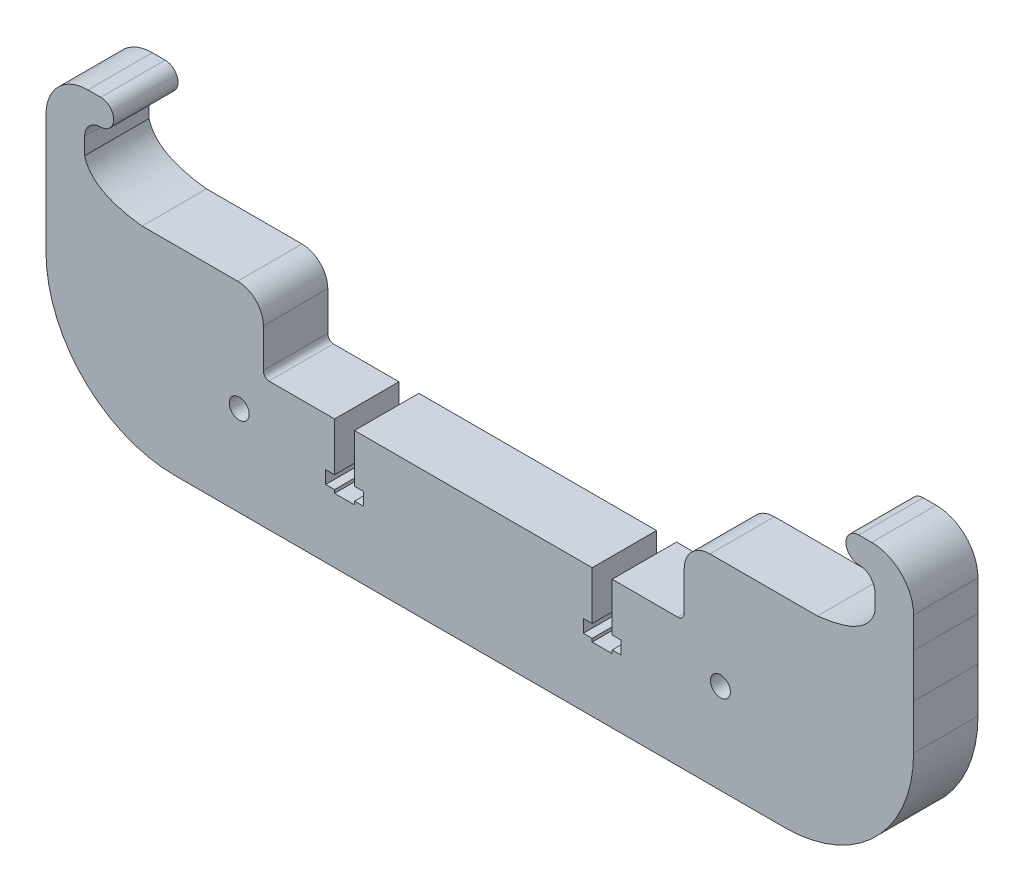
SolidWorks part; units mm, degrees
ref_plane "Płaszczyzna przednia" through (0, 0, 0) normal (0, 0, 1) x (1, 0, 0)
ref_plane "Płaszczyzna górna" through (0, 0, 0) normal (0, 1, 0) x (1, 0, 0)
ref_plane "Płaszczyzna prawa" through (0, 0, 0) normal (1, 0, 0) x (0, 0, -1)
sketch "Szkic1" plane through (0, 0, 0) normal (0, 0, 1) x (1, 0, 0)
  line L7 (587.4141, -426.2962) -> (650.8826, -426.2962)
  line L11 (552.8031, -407.6962) -> (552.8031, -419.2962)
  line L12 (561.3031, -401.1962) -> (559.3031, -401.1962)
  line L13 (567.725, -415.2962) -> (582.5551, -415.2962)
  line L14 (586.5551, -425.2962) -> (586.5551, -419.2962)
  line L15 (651.8852, -425.2936) -> (651.8852, -419.2962)
  line L16 (672.5705, -415.2962) -> (655.8852, -415.2962)
  line L17 (681.4924, -407.6962) -> (681.4924, -410.3096)
  line L18 (678.9924, -401.1962) -> (680.9924, -401.1962)
  line L20 (687.4924, -407.6962) -> (687.4924, -412.4993)
  line L21 (687.4978, -419.2962) -> (687.4924, -412.4993)
  line L22 (572.8031, -439.2962) -> (667.4978, -439.2962) construction
  line L23 (558.8031, -407.6962) -> (558.8031, -410.3096)
  line L28 (572.8031, -439.2962) -> (667.4978, -439.2962)
  arc A3 (667.4978, -439.2962) -> (687.4978, -419.2962) centre (667.4978, -419.2962) ccw construction
  arc A5 (552.8031, -419.2962) -> (572.8031, -439.2962) centre (572.8031, -419.2962) ccw construction
  arc A6 (667.4978, -439.2962) -> (687.4978, -419.2962) centre (667.4978, -419.2962) ccw
  arc A7 (552.8031, -419.2962) -> (572.8031, -439.2962) centre (572.8031, -419.2962) ccw
  arc A12 (559.3031, -401.1962) -> (552.8031, -407.6962) centre (559.3031, -407.6962) ccw
  arc A13 (561.3031, -405.1962) -> (561.3031, -401.1962) centre (561.3031, -403.1962) ccw
  arc A14 (561.3031, -405.1962) -> (558.8031, -407.6962) centre (561.3031, -407.6962) ccw
  arc A15 (586.5551, -419.2962) -> (582.5551, -415.2962) centre (582.5551, -419.2962) ccw
  arc A16 (655.8852, -415.2962) -> (651.8852, -419.2962) centre (655.8852, -419.2962) ccw
  arc A17 (681.4924, -407.6962) -> (678.9924, -405.1962) centre (678.9924, -407.6962) ccw
  arc A18 (678.9924, -401.1962) -> (678.9924, -405.1962) centre (678.9924, -403.1962) ccw
  arc A19 (687.4924, -407.6962) -> (680.9924, -401.1962) centre (680.9924, -407.6962) ccw
  arc A20 (651.8852, -425.2936) -> (650.8826, -426.2962) centre (650.8826, -425.2936) cw
  arc A21 (586.5551, -425.2962) -> (587.4141, -426.2962) centre (587.4846, -425.3667) ccw
  parabola Q2 (567.725, -415.2962) -> (558.8031, -410.3096) focus (561.3063, -410.1181) apex (559.1464, -411.2024)
  parabola Q3 (672.5705, -415.2962) -> (681.4924, -410.3096) focus (678.9892, -410.1181) apex (681.1491, -411.2024)
  point P0 (567.8031, -401.1962)
  point P20 (567.8031, -405.1962)
  point P21 (559.3031, -405.1962)
  point P30 (679.1031, -405.1962)
  point P31 (670.6031, -405.1962)
extrude "Dodanie-wyciągnięcie1" add sketch "Szkic1" along normal blind 10 contours L7 A20 L15 A16 L16 Q3 L17 A17 A18 L18 A19 L20 L21 A6 L28 A7 L11 A12 L12 A13 A14 L23 Q2 L13 A15 L14 A21
sketch "Szkic2" plane through (0, 0, 10) normal (0, 0, 1) x (1, 0, 0)
  line L0 (687.4978, -419.2962) -> (687.4924, -412.4993) construction
  line L1 (552.8031, -407.6962) -> (552.8031, -419.2962) construction
  circle A2 centre (657.508, -432.2754) radius 1.55
  circle A3 centre (582.8031, -432.2962) radius 1.55
  dimension "D1" = 30
  dimension "D2" = 30
extrude "Wytnij-wyciągnięcie1" cut sketch "Szkic2" against normal blind 10
sketch "Szkic3" plane through (0, 0, 0) normal (0, 0, -1) x (-1, 0, 0)
  line L0 (-600.6991, -426.2962) -> (-600.6991, -433.7962) construction
  line L1 (-597.5991, -433.7962) -> (-597.5991, -426.2962) construction
  line L2 (-600.6991, -433.7962) -> (-602.0741, -433.7962) construction
  line L3 (-602.0741, -433.7962) -> (-602.0741, -435.7962) construction
  line L4 (-602.0741, -435.7962) -> (-600.6991, -435.7962) construction
  line L5 (-600.6991, -435.7962) -> (-600.6991, -436.2962) construction
  line L6 (-600.6991, -436.2962) -> (-597.5991, -436.2962) construction
  line L7 (-597.5991, -435.7962) -> (-596.2241, -435.7962) construction
  line L8 (-597.5991, -436.2962) -> (-597.5991, -435.7962) construction
  line L9 (-596.2241, -435.7962) -> (-596.2241, -433.7962) construction
  line L10 (-596.2241, -433.7962) -> (-597.5991, -433.7962) construction
  line L11 (-600.6991, -426.2962) -> (-600.6991, -433.7962)
  line L12 (-597.5991, -433.7962) -> (-597.5991, -426.2962)
  line L13 (-600.6991, -433.7962) -> (-602.0741, -433.7962)
  line L14 (-602.0741, -433.7962) -> (-602.0741, -435.7962)
  line L15 (-602.0741, -435.7962) -> (-600.6991, -435.7962)
  line L16 (-600.6991, -435.7962) -> (-600.6991, -436.2962)
  line L17 (-600.6991, -436.2962) -> (-597.5991, -436.2962)
  line L18 (-597.5991, -435.7962) -> (-596.2241, -435.7962)
  line L19 (-597.5991, -436.2962) -> (-597.5991, -435.7962)
  line L20 (-596.2241, -435.7962) -> (-596.2241, -433.7962)
  line L21 (-596.2241, -433.7962) -> (-597.5991, -433.7962)
  line L22 (-640.6991, -426.2962) -> (-640.6991, -433.7962) construction
  line L23 (-640.6991, -433.7962) -> (-642.0741, -433.7962) construction
  line L24 (-642.0741, -433.7962) -> (-642.0741, -435.7962) construction
  line L25 (-642.0741, -435.7962) -> (-640.6991, -435.7962) construction
  line L26 (-640.6991, -435.7962) -> (-640.6991, -436.2962) construction
  line L27 (-640.6991, -436.2962) -> (-637.5991, -436.2962) construction
  line L28 (-637.5991, -436.2962) -> (-637.5991, -435.7962) construction
  line L29 (-637.5991, -435.7962) -> (-636.2241, -435.7962) construction
  line L30 (-636.2241, -435.7962) -> (-636.2241, -433.7962) construction
  line L31 (-636.2241, -433.7962) -> (-637.5991, -433.7962) construction
  line L32 (-637.5991, -433.7962) -> (-637.5991, -426.2962) construction
  line L33 (-640.6991, -426.2962) -> (-640.6991, -433.7962)
  line L34 (-640.6991, -433.7962) -> (-642.0741, -433.7962)
  line L35 (-642.0741, -433.7962) -> (-642.0741, -435.7962)
  line L36 (-642.0741, -435.7962) -> (-640.6991, -435.7962)
  line L37 (-640.6991, -435.7962) -> (-640.6991, -436.2962)
  line L38 (-640.6991, -436.2962) -> (-637.5991, -436.2962)
  line L39 (-637.5991, -436.2962) -> (-637.5991, -435.7962)
  line L40 (-637.5991, -435.7962) -> (-636.2241, -435.7962)
  line L41 (-636.2241, -435.7962) -> (-636.2241, -433.7962)
  line L42 (-636.2241, -433.7962) -> (-637.5991, -433.7962)
  line L43 (-637.5991, -433.7962) -> (-637.5991, -426.2962)
  line L44 (-640.6991, -426.2962) -> (-637.5991, -426.2962)
  line L45 (-600.6991, -426.2962) -> (-597.5991, -426.2962)
extrude "Wytnij-wyciągnięcie2" cut sketch "Szkic3" against normal blind 10
sketch "Szkic4" plane through (0, 0, 0) normal (0, 0, -1) x (-1, 0, 0)
  line L1 (-572.8031, -446.2962) -> (-667.4978, -446.2962)
  line L2 (-600.6991, -426.2962) -> (-637.5991, -426.2962) construction
  line L3 (-687.4978, -426.2962) -> (-687.4978, -419.2962)
  line L4 (-572.8031, -439.2962) -> (-667.4978, -439.2962) construction
  line L5 (-572.8031, -439.2962) -> (-667.4978, -439.2962)
  line L7 (-552.8031, -407.6962) -> (-552.8031, -419.2962) construction
  line L8 (-552.8031, -419.2962) -> (-552.8031, -426.2962)
  arc A2 (-572.8031, -446.2962) -> (-552.8031, -426.2962) centre (-572.8031, -426.2962) ccw
  arc A3 (-687.4978, -426.2962) -> (-667.4978, -446.2962) centre (-667.4978, -426.2962) ccw
  arc A4 (-572.8031, -439.2962) -> (-552.8031, -419.2962) centre (-572.8031, -419.2962) ccw construction
  arc A5 (-687.4978, -419.2962) -> (-667.4978, -439.2962) centre (-667.4978, -419.2962) ccw construction
  arc A6 (-572.8031, -439.2962) -> (-552.8031, -419.2962) centre (-572.8031, -419.2962) ccw
  arc A7 (-687.4978, -419.2962) -> (-667.4978, -439.2962) centre (-667.4978, -419.2962) ccw
  dimension "D1" = 20
  dimension "D2" = 20
  dimension "D3" = 20
extrude "Dodanie-wyciągnięcie2" add sketch "Szkic4" against normal blind 10
equation "\"tolerancja_wpusy\"=0.2"
equation "\"dlugosc_wpustu_duzy\"=20"
equation "\"srednica_otworu_M3\"=3.1"
equation "\"szerokosc_nogi_T\"=3.1"
equation "\"dlugosc_T_30\"=11"
equation "\"grubosc_na_nakretke_kwadrat\"=2"
equation "\"szerokosc_na_nakretke_kwadrat\"=5.85"
equation "\"wyokosc_nadstawki_T\"=0.5"
equation "\"dlugosc_T_20_6\"=14"
